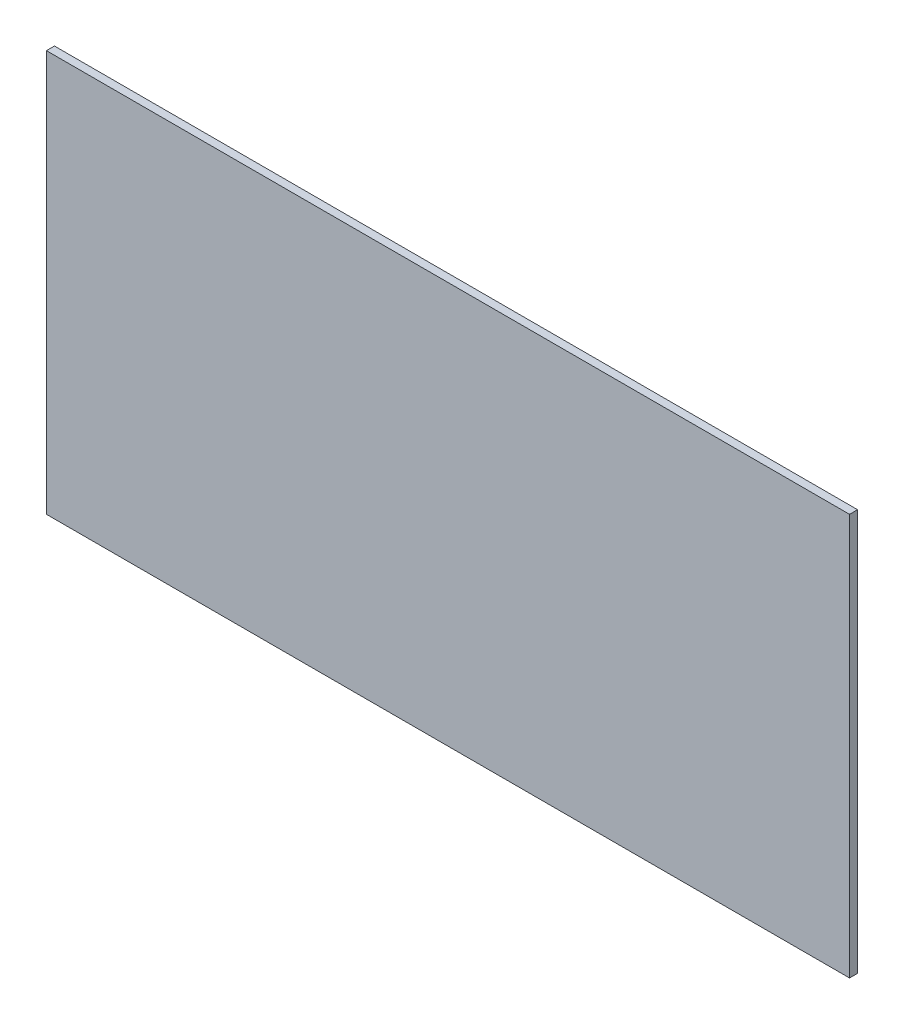
SolidWorks part; units mm, degrees
ref_plane "Front Plane" through (0, 0, 0) normal (0, 0, 1) x (1, 0, 0)
ref_plane "Top Plane" through (0, 0, 0) normal (0, 1, 0) x (1, 0, 0)
ref_plane "Right Plane" through (0, 0, 0) normal (1, 0, 0) x (0, 0, -1)
sketch "Sketch2" plane through (0, 0, 0) normal (0, 1, 0) x (1, 0, 0)
  line L1 (-500, 5) -> (500, 5)
  line L2 (-500, 5) -> (-500, -5)
  line L3 (-500, -5) -> (500, -5)
  line L4 (500, 5) -> (500, -5)
  line L5 (-500, 5) -> (500, -5) construction
  line L6 (-500, -5) -> (500, 5) construction
  point P0 (0, 0)
  dimension "D1" = 1000
  dimension "D2" = 10
extrude "Boss-Extrude1" add sketch "Sketch2" along normal blind 500
